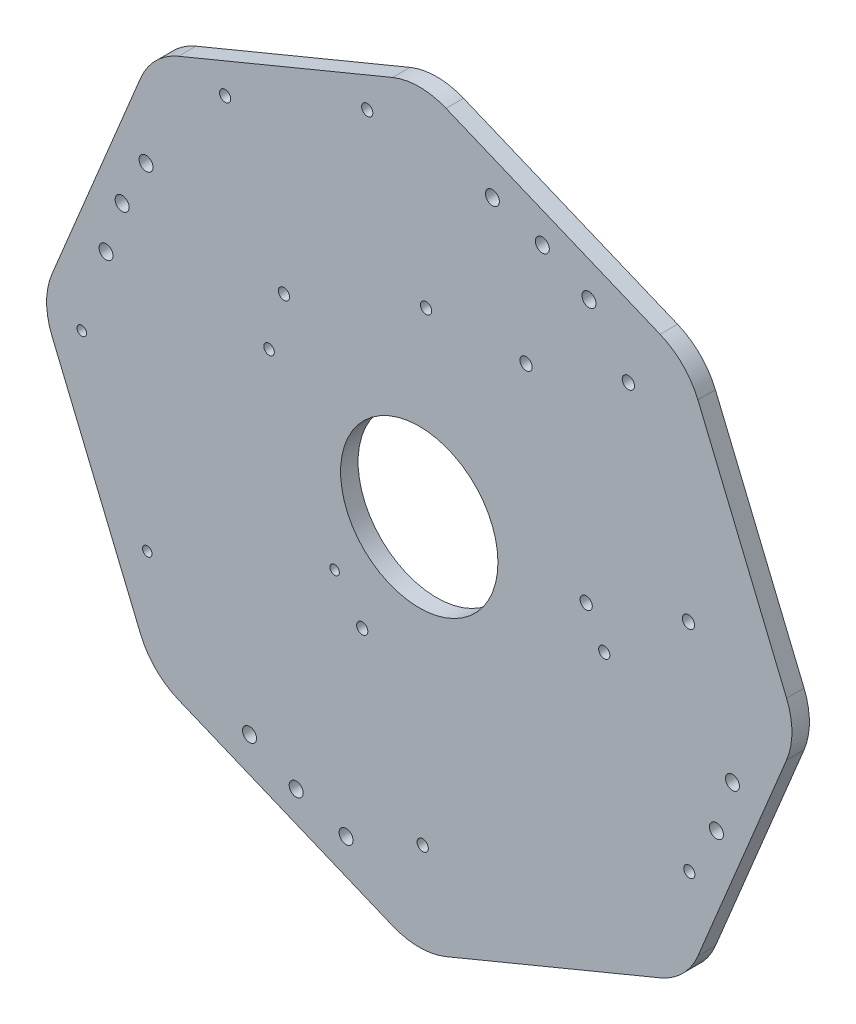
SolidWorks part; units mm, degrees
ref_plane "前视基准面" through (0, 0, 0) normal (0, 0, 1) x (1, 0, 0)
ref_plane "上视基准面" through (0, 0, 0) normal (0, 1, 0) x (1, 0, 0)
ref_plane "右视基准面" through (0, 0, 0) normal (1, 0, 0) x (0, 0, -1)
sketch "草图1" plane through (0, 0, 0) normal (0, 0, 1) x (1, 0, 0)
  line L0 (0, 121.5223) -> (0, -117.9323) construction
  line L1 (-126.6637, 0) -> (129.3981, 0) construction
  line L2 (0, 108.2392) -> (-76.5367, 76.5367)
  line L3 (-76.5367, 76.5367) -> (-108.2392, 0)
  line L4 (-108.2392, 0) -> (-76.5367, -76.5367)
  line L5 (-76.5367, -76.5367) -> (0, -108.2392)
  line L6 (0, -108.2392) -> (76.5367, -76.5367)
  line L7 (76.5367, -76.5367) -> (108.2392, 0)
  line L8 (108.2392, 0) -> (76.5367, 76.5367)
  line L9 (76.5367, 76.5367) -> (0, 108.2392)
  line L10 (-17.4834, -36.185) -> (0.9849, -80.7715) construction
  line L11 (-17.4834, -36.185) -> (58.7828, -4.5945) construction
  line L12 (0.9849, -80.7715) -> (77.2511, -49.181) construction
  line L13 (58.7828, -4.5945) -> (77.2511, -49.181) construction
  line L14 (-38.2683, -92.388) -> (38.2683, 92.388) construction
  line L15 (-92.388, 38.2683) -> (92.388, -38.2683) construction
  line L16 (-55.5322, 76.5779) -> (-38.6942, 35.9272) construction
  line L17 (-55.5322, 76.5779) -> (-14.8815, 93.416) construction
  line L18 (-38.6942, 35.9272) -> (1.9565, 52.7653) construction
  line L19 (-14.8815, 93.416) -> (1.9565, 52.7653) construction
  line L20 (-38.2683, 92.388) -> (0, 0) construction
  line L25 (-92.388, -38.2683) -> (0, 0) construction
  line L26 (30.5432, 53.2826) -> (59.8028, 63.2164) construction
  line L27 (30.5432, 53.2826) -> (47.7425, 2.6226) construction
  line L28 (59.8028, 63.2164) -> (77.0022, 12.5564) construction
  line L29 (47.7425, 2.6226) -> (77.0022, 12.5564) construction
  line L30 (-96.5431, -2.1057) -> (-77.7916, -47.3758) construction
  line L31 (-96.5431, -2.1057) -> (-42.9581, 20.0899) construction
  line L32 (-77.7916, -47.3758) -> (-24.2066, -25.1802) construction
  line L33 (-42.9581, 20.0899) -> (-24.2066, -25.1802) construction
  circle A0 centre (0, 0) radius 100 construction
  circle A2 centre (0.9849, -80.7715) radius 1.6
  circle A3 centre (77.2511, -49.181) radius 1.6
  circle A5 centre (-35.2069, -84.9969) radius 2
  circle A6 centre (84.9969, -35.2069) radius 2
  circle A7 centre (35.2069, 84.9969) radius 2
  circle A8 centre (-84.9969, 35.2069) radius 2
  circle A9 centre (-16.3101, -35.699) radius 1.6
  circle A10 centre (52.9162, -7.0246) radius 1.6
  circle A11 centre (0, 0) radius 22.5
  circle A12 centre (-55.5322, 76.5779) radius 1.6
  circle A13 centre (-38.6942, 35.9272) radius 1.6
  circle A14 centre (1.9565, 52.7653) radius 1.6
  circle A15 centre (-14.8815, 93.416) radius 1.6
  circle A25 centre (0, 0) radius 92 construction
  circle A27 centre (89.5883, -20.9269) radius 2
  circle A28 centre (-20.9269, -89.5883) radius 2
  circle A29 centre (-89.5883, 20.9269) radius 2
  circle A30 centre (20.9269, 89.5883) radius 2
  circle A31 centre (30.5432, 53.2826) radius 1.75
  circle A32 centre (59.8028, 63.2164) radius 1.75
  circle A33 centre (47.7425, 2.6226) radius 1.75
  circle A34 centre (77.0022, 12.5564) radius 1.75
  circle A35 centre (-96.5431, -2.1057) radius 1.35
  circle A36 centre (-77.7916, -47.3758) radius 1.35
  circle A37 centre (-42.9581, 20.0899) radius 1.5
  circle A38 centre (-24.2066, -25.1802) radius 1.35
  circle A39 centre (-48.551, -78.146) radius 2
  circle A40 centre (-78.146, 48.551) radius 2
  circle A41 centre (48.551, 78.146) radius 2
  circle A43 centre (78.146, -48.551) radius 2 [skipped]
  point P76 (0, 0)
  point P85 (0, 0)
  dimension "D6" = 3.2
  dimension "D7" = 3.2
  dimension "D8" = 3.2
  dimension "D9" = 3.2
  dimension "D10" = 4
  dimension "D11" = 4
  dimension "D12" = 4
  dimension "D13" = 4
  dimension "D14" = 8
  dimension "D15" = 8
  dimension "D16" = 8
  dimension "D17" = 8
  dimension "D20" = 45
  dimension "D25" = 3.2
  dimension "D26" = 3.2
  dimension "D27" = 3.2
  dimension "D28" = 3.2
  dimension "D29" = 58
  dimension "D30" = 49
  dimension "D31" = 10
  dimension "D32" = 35
  dimension "D37" = 92
  dimension "D38" = 15
  dimension "D39" = 4
  dimension "D43" = 3.5
  dimension "D44" = 3.5
  dimension "D45" = 3.5
  dimension "D46" = 3.5
  dimension "D33" = 92
  dimension "D34" = 15
  dimension "D35" = 4
  dimension "D1" = 200
  dimension "D2" = 48.26
  dimension "D3" = 82.55
  dimension "D4" = 70
  dimension "D5" = 25
  dimension "D18" = 1.27
  dimension "D19" = 6.35
  dimension "D21" = 44
  dimension "D22" = 44
  dimension "D23" = 8
  dimension "D24" = 22
  dimension "D36" = 4
  dimension "D41" = 53.5
  dimension "D42" = 30.9
  dimension "D40" = 4
extrude "凸台-拉伸1" add sketch "草图1" along normal blind 5
fillet "圆角1" radius 20 8 edges at (-76.5367, 76.5367, 2.5) (0, 108.2392, 2.5) (76.5367, 76.5367, 2.5) (108.2392, 0, 2.5) (76.5367, -76.5367, 2.5) (0, -108.2392, 2.5) (-76.5367, -76.5367, 2.5) (-108.2392, 0, 2.5)
